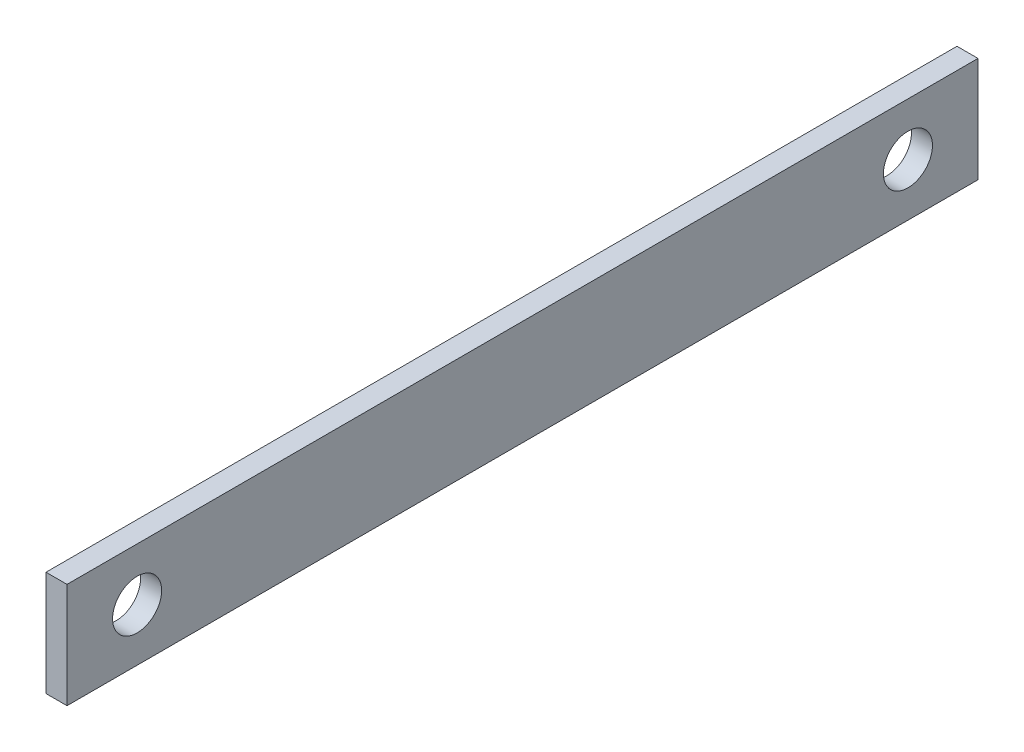
SolidWorks part; units mm, degrees
material "ASTM A36 Steel"
ref_plane "Front Plane" through (0, 0, 0) normal (0, 0, 1) x (1, 0, 0)
ref_plane "Top Plane" through (0, 0, 0) normal (0, 1, 0) x (1, 0, 0)
ref_plane "Right Plane" through (0, 0, 0) normal (1, 0, 0) x (0, 0, -1)
sketch "Sketch1" plane through (0, 0, 0) normal (1, 0, 0) x (0, 0, -1)
  line L1 (-130, -15) -> (130, -15)
  line L2 (-130, -15) -> (-130, 15)
  line L3 (-130, 15) -> (130, 15)
  line L4 (130, -15) -> (130, 15)
  line L5 (-130, -15) -> (130, 15) construction
  line L6 (-130, 15) -> (130, -15) construction
  circle A0 centre (-110, 0) radius 7
  circle A1 centre (110, 0) radius 7
  point P0 (0, 0)
  dimension "D3" = 14
  dimension "D4" = 14
  dimension "D5" = 20
  dimension "D6" = 20
  dimension "D1" = 30
  dimension "D2" = 260
extrude "Boss-Extrude1" add sketch "Sketch1" along normal blind 6
